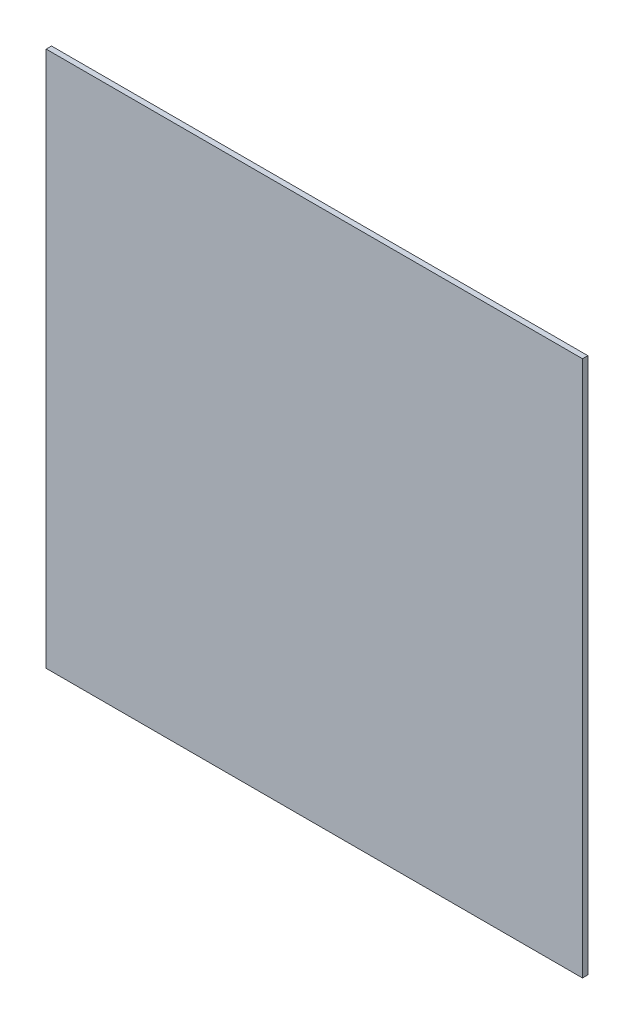
SolidWorks part; units mm, degrees
ref_plane "Front Plane" through (0, 0, 0) normal (0, 0, 1) x (1, 0, 0)
ref_plane "Top Plane" through (0, 0, 0) normal (0, 1, 0) x (1, 0, 0)
ref_plane "Right Plane" through (0, 0, 0) normal (1, 0, 0) x (0, 0, -1)
sketch "Sketch1" plane through (0, 0, 0) normal (0, 0, 1) x (1, 0, 0)
  line L0 (-79.2175, 76.6571) -> (220.7825, 76.6571)
  line L1 (220.7825, 76.6571) -> (220.7825, -223.3429)
  line L2 (220.7825, -223.3429) -> (-79.2175, -223.3429)
  line L3 (-79.2175, -223.3429) -> (-79.2175, 76.6571)
  dimension "D1" = 300
  dimension "D2" = 300
extrude "Boss-Extrude1" add sketch "Sketch1" along normal blind 3
